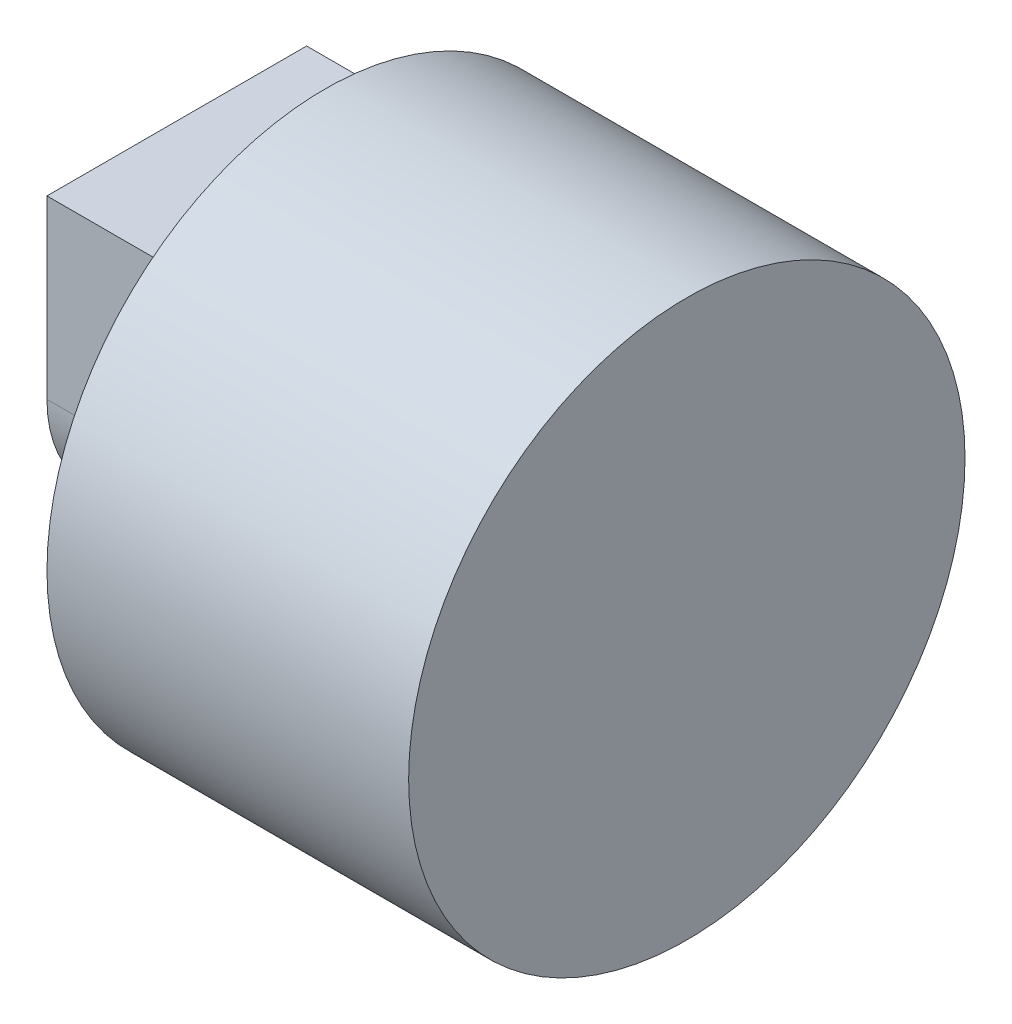
SolidWorks part; units mm, degrees
ref_plane "Front Plane" through (0, 0, 0) normal (0, 0, 1) x (1, 0, 0)
ref_plane "Top Plane" through (0, 0, 0) normal (0, 1, 0) x (1, 0, 0)
ref_plane "Right Plane" through (0, 0, 0) normal (1, 0, 0) x (0, 0, -1)
sketch "Sketch1" plane through (0, 0, 0) normal (0, 0, 1) x (1, 0, 0)
  line L0 (0, 0) -> (27.7266, 0) construction
  line L1 (0, 0) -> (0, 15)
  line L2 (0, 15) -> (19.5, 15)
  line L3 (19.5, 15) -> (19.5, 0)
  line L4 (0, 0) -> (19.5, 0)
  dimension "D1" = 19.5
  dimension "D2" = 15
revolve "Revolve1" add sketch "Sketch1" angle 360 about L0
sketch "Sketch2" plane through (0, 0, 0) normal (-1, 0, 0) x (0, 0, 1)
  line L0 (-7, 0) -> (-7, 9.5)
  line L1 (-7, 9.5) -> (7, 9.5)
  line L2 (7, 0) -> (7, 9.5)
  line L3 (-3, 0) -> (-3, 5.5)
  line L4 (-3, 5.5) -> (3, 5.5)
  line L5 (3, 0) -> (3, 5.5)
  arc A0 (-7, 0) -> (7, 0) centre (0, 0) ccw
  arc A1 (-3, 0) -> (3, 0) centre (0, 0) ccw
  point P5 (0, -7)
  point P11 (0, -3)
  dimension "D1" = 14
  dimension "D3" = 6
  dimension "D2" = 16.5
  dimension "D4" = 8.5
extrude "Boss-Extrude1" add sketch "Sketch2" along normal blind 8
sketch "Sketch3" plane through (0, 0, 0) normal (-1, 0, 0) x (0, 0, 1)
  circle A0 centre (0, 0) radius 3
extrude "Cut-Extrude1" cut sketch "Sketch3" against normal blind 10
